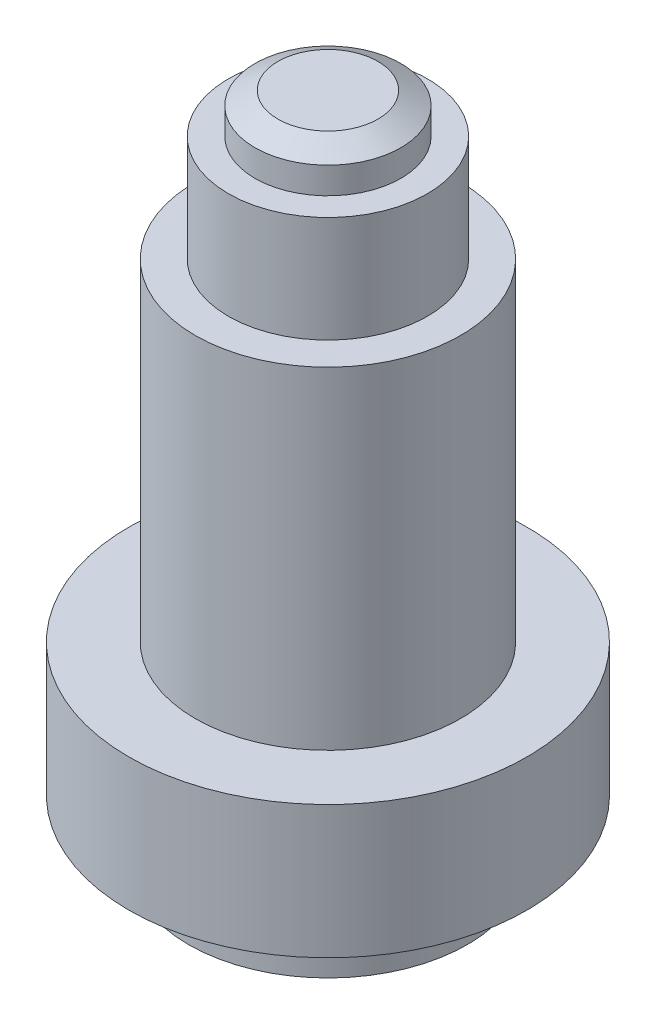
SolidWorks part; units mm, degrees
ref_plane "Front Plane" through (0, 0, 0) normal (0, 0, 1) x (1, 0, 0)
ref_plane "Top Plane" through (0, 0, 0) normal (0, 1, 0) x (1, 0, 0)
ref_plane "Right Plane" through (0, 0, 0) normal (1, 0, 0) x (0, 0, -1)
sketch "Sketch1" plane through (0, 0, 0) normal (0, 1, 0) x (1, 0, 0)
  circle A0 centre (0, 0) radius 10.5
extrude "Boss-Extrude1" add sketch "Sketch1" along normal blind 4.5
sketch "Sketch2" plane through (0, 4.5, 0) normal (0, 1, 0) x (1, 0, 0)
  circle A0 centre (0, 0) radius 15
extrude "Boss-Extrude2" add sketch "Sketch2" along normal blind 10
sketch "Sketch3" plane through (0, 14.5, 0) normal (0, 1, 0) x (1, 0, 0)
  circle A0 centre (0, 0) radius 10
extrude "Boss-Extrude3" add sketch "Sketch3" along normal blind 25
sketch "Sketch4" plane through (0, 39.5, 0) normal (0, 1, 0) x (1, 0, 0)
  circle A0 centre (0, 0) radius 7.5
extrude "Boss-Extrude4" add sketch "Sketch4" along normal blind 8
sketch "Sketch5" plane through (0, 47.5, 0) normal (0, 1, 0) x (1, 0, 0)
  circle A0 centre (0, 0) radius 5.5
extrude "Boss-Extrude5" add sketch "Sketch5" along normal blind 3
chamfer "Chamfer1" distance 1 angle 60 1 edges at (0, 50.5, 5.5)
